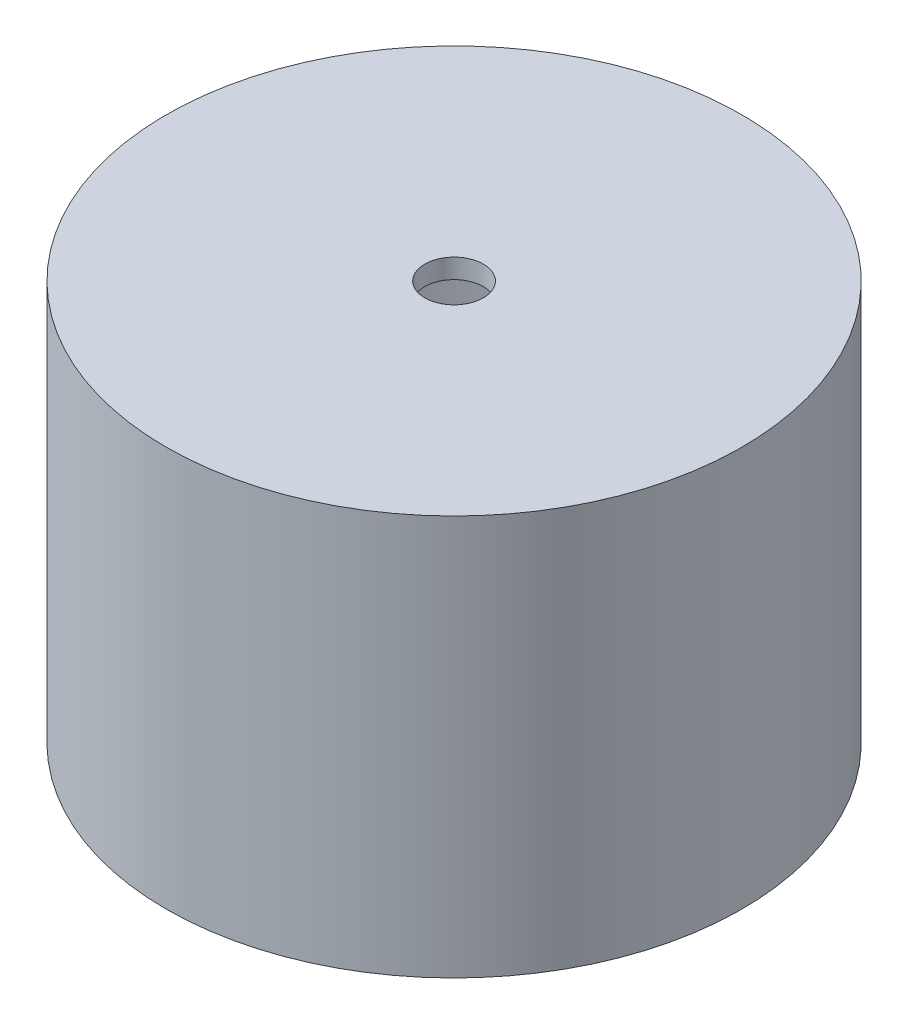
SolidWorks part; units mm, degrees
ref_plane "Front Plane" through (0, 0, 0) normal (0, 0, 1) x (1, 0, 0)
ref_plane "Top Plane" through (0, 0, 0) normal (0, 1, 0) x (1, 0, 0)
ref_plane "Right Plane" through (0, 0, 0) normal (1, 0, 0) x (0, 0, -1)
other "Center of Mass"
sketch "Sketch1" plane through (0, 0, 0) normal (0, 1, 0) x (1, 0, 0)
  circle A0 centre (0, 0) radius 37.465
  circle A2 centre (0, 0) radius 3.81
extrude "Boss-Extrude1" add sketch "Sketch1" against normal blind 2.54
sketch "Sketch2" plane through (0, -2.54, 0) normal (0, -1, 0) x (1, 0, 0)
  line L0 (1.397, 0) -> (-1.397, 0) construction
  circle A1 centre (0, 18.7325) radius 5.58
  circle A3 centre (0, -18.7325) radius 5.58
  circle A7 centre (0, 18.7325) radius 9.39
  circle A8 centre (0, -18.7325) radius 9.39
extrude "Boss-Extrude2" add sketch "Sketch2" along normal blind 50.8
sketch "Sketch3" plane through (0, -2.54, 0) normal (0, -1, 0) x (1, 0, 0)
  circle A1 centre (0, 0) radius 37.465
  circle A2 centre (0, 0) radius 36.165
extrude "Boss-Extrude3" add sketch "Sketch3" along normal up to surface (49.53 mm away)
sketch "Sketch5" plane through (0, -2.54, 0) normal (0, -1, 0) x (1, 0, 0)
  circle A0 centre (0, 18.7325) radius 5.58
  circle A1 centre (0, -18.7325) radius 5.58
extrude "Boss-Extrude4" add sketch "Sketch5" along normal blind 41.91
sketch "Sketch6" plane through (0, 0, 0) normal (0, 0, 1) x (1, 0, 0)
  line L0 (0, -8.622) -> (0, 176.142)
  line L1 (-39.37, 176.142) -> (39.37, 176.142) construction
